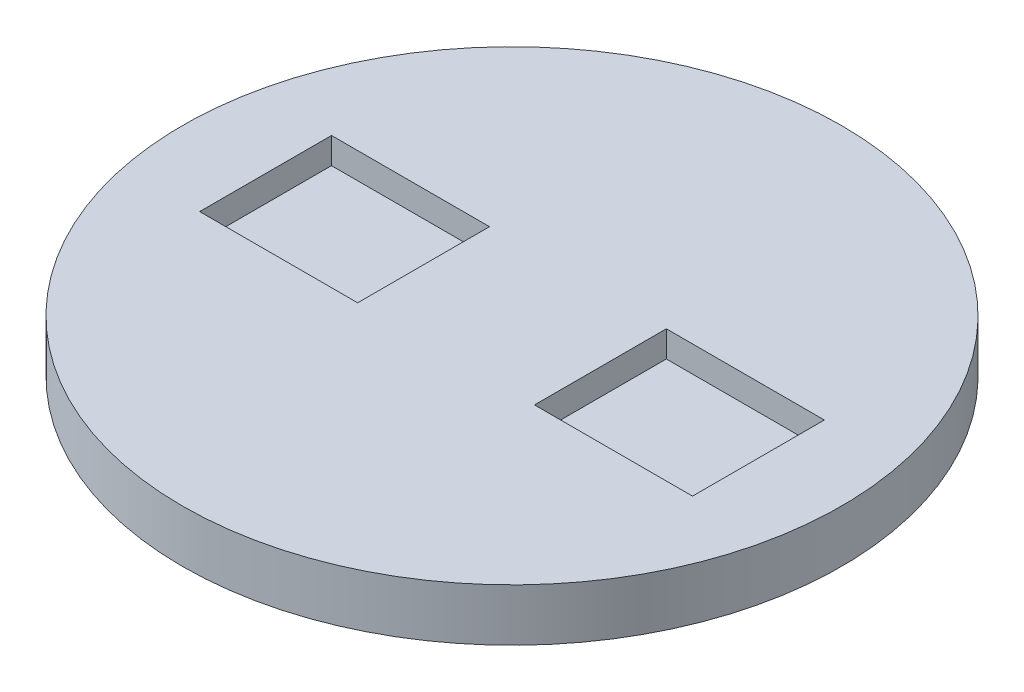
SolidWorks part; units mm, degrees
ref_plane "前视基准面" through (0, 0, 0) normal (0, 0, 1) x (1, 0, 0)
ref_plane "上视基准面" through (0, 0, 0) normal (0, 1, 0) x (1, 0, 0)
ref_plane "右视基准面" through (0, 0, 0) normal (1, 0, 0) x (0, 0, -1)
sketch "草图1" plane through (0, 0, 0) normal (0, 1, 0) x (1, 0, 0)
  circle A0 centre (0, 0) radius 62.9894
extrude "凸台-拉伸1" add sketch "草图1" along normal blind 10
sketch "草图2" plane through (0, 10, 0) normal (0, 1, 0) x (1, 0, 0)
  line L0 (0, 76.1897) -> (0, -80.2483) construction
  line L1 (-47.1, 12.6) -> (47.1, 12.6)
  line L2 (-47.1, 12.6) -> (-47.1, -12.6)
  line L3 (-47.1, -12.6) -> (47.1, -12.6)
  line L4 (47.1, 12.6) -> (47.1, -12.6)
  line L5 (-90.3946, 0) -> (103.3081, 0) construction
  line L6 (-16.9, 12.6) -> (-16.9, -12.6)
  line L7 (16.9, 12.6) -> (16.9, -12.6)
  point P9 (-47.1, 0)
  point P10 (0, 12.6)
  dimension "D1" = 25.2
  dimension "D2" = 94.2
  dimension "D3" = 30.2
  dimension "D4" = 30.2
extrude "切除-拉伸1" cut sketch "草图2" against normal blind 5 contours L6 L1 L2 L3 | L1 L7 L3 L4
